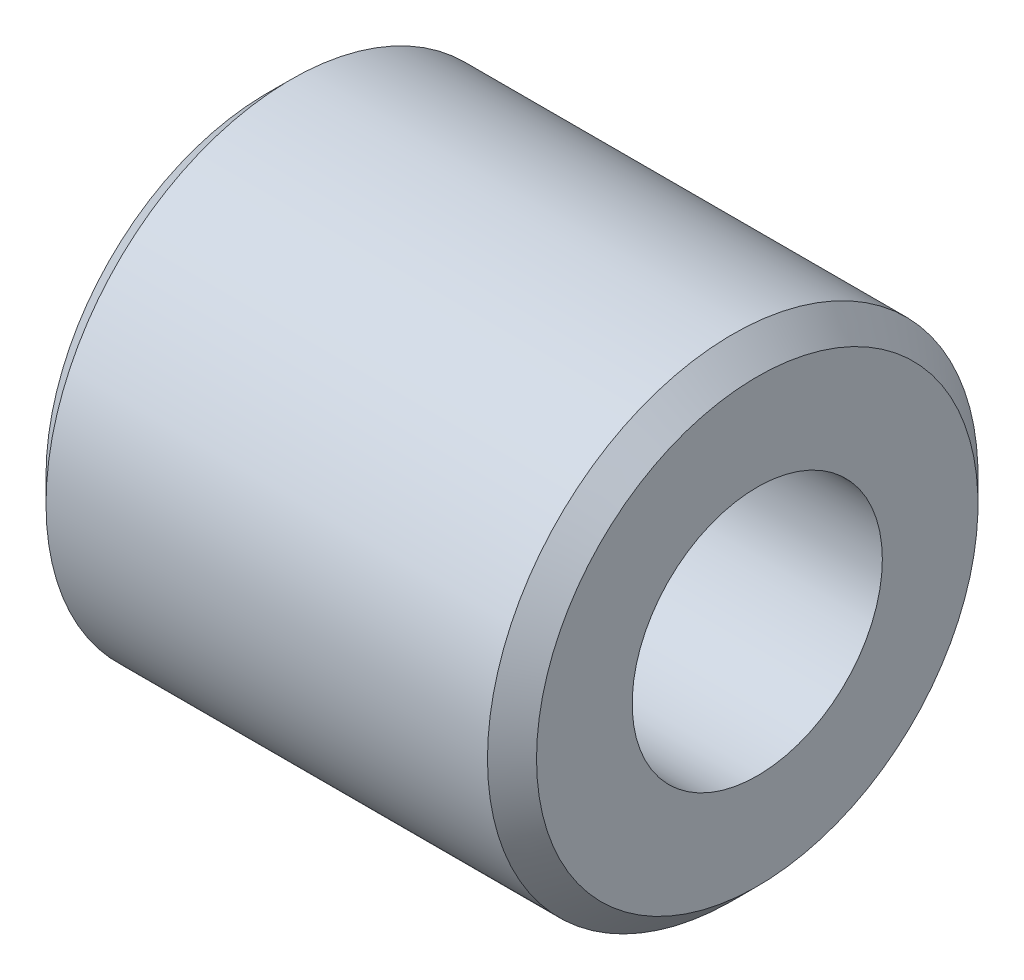
SolidWorks part; units mm, degrees
ref_plane "Face" through (0, 0, 0) normal (0, 0, 1) x (1, 0, 0)
ref_plane "Dessus" through (0, 0, 0) normal (0, 1, 0) x (1, 0, 0)
ref_plane "Droite" through (0, 0, 0) normal (1, 0, 0) x (0, 0, -1)
sketch "Esquisse1" plane through (0, 0, 0) normal (0, 0, 1) x (1, 0, 0)
  line L0 (0, 0) -> (-20, 0)
  line L1 (-20, 0) -> (-20, 9)
  line L2 (-19, 10) -> (-1, 10)
  line L3 (0, 9) -> (0, 0)
  line L4 (-1, 10) -> (0, 9)
  line L5 (-20, 9) -> (-19, 10)
  line L6 (-22.0391, 0) -> (0, 0) construction
  point P2 (-20, 10)
  point P3 (0, 10)
  dimension "D1" = 10
  dimension "D2" = 20
  dimension "D5" = 1
  dimension "D6" = 1
revolve "Base-Révolution" add sketch "Esquisse1" angle 360 about L6
hole_wizard "Trou taraudé M12x1.751" positions "Esquisse3" profile "Esquisse2" tap size "M12x1.75" standard "ISO" end condition through all
sketch "Esquisse3" plane through (0, 0, 0) normal (1, 0, 0) x (0, 0, -1)
  circle A0 centre (0, 0) radius 9 construction
  point P0 (0, 0)
sketch "Esquisse2" plane through (0, 0, 0) normal (0, 1, 0) x (0, 0, -1)
  line L0 (0, 0) -> (0, 20)
  line L1 (0, 20) -> (5.1, 20)
  line L2 (5.1, 20) -> (5.1, 0)
  line L5 (5.1, 0) -> (0, 0)
  line L11 (0, -6.35) -> (0, 107.95) construction
  dimension "Diamètre du perçage jusqu'au prochain" = 10.2
  dimension "Profondeur du perçage jusqu'au prochain" = 20
cosmetic thread "Représentation de filetage1" parameters "D1"=20, "D2"=12
